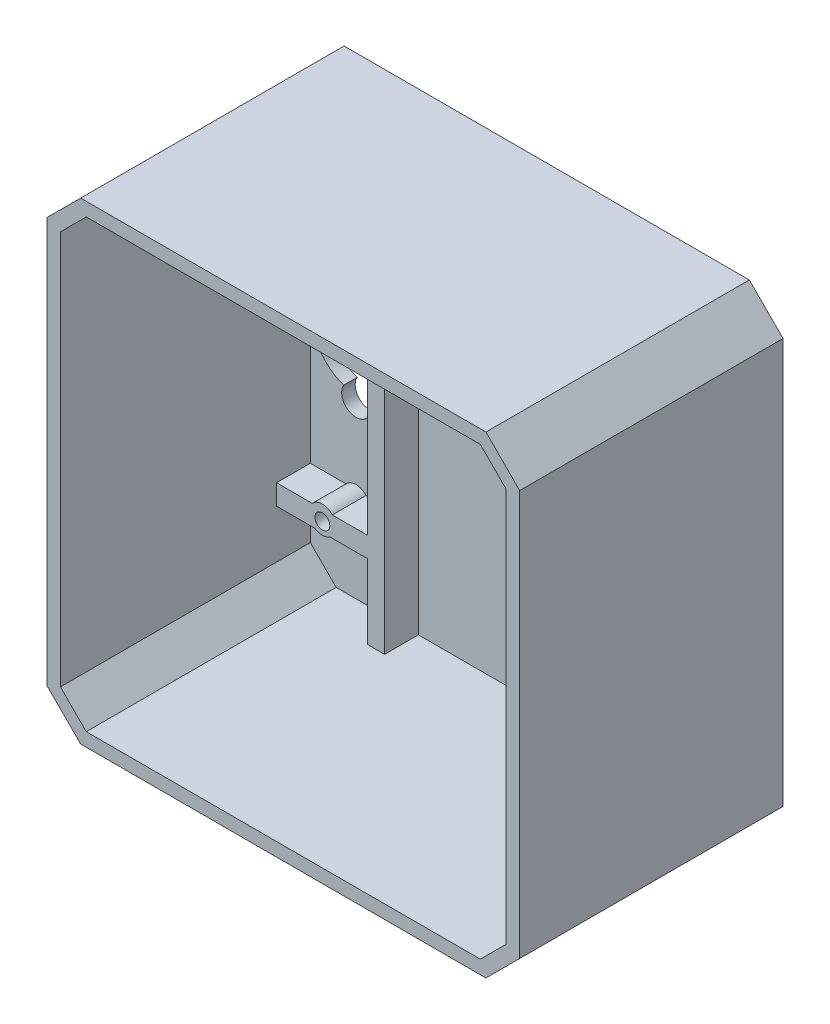
SolidWorks part; units mm, degrees
ref_plane "Front Plane" through (0, 0, 0) normal (0, 0, 1) x (1, 0, 0)
ref_plane "Top Plane" through (0, 0, 0) normal (0, 1, 0) x (1, 0, 0)
ref_plane "Right Plane" through (0, 0, 0) normal (1, 0, 0) x (0, 0, -1)
sketch "Sketch1" plane through (0, 0, 0) normal (0, 0, 1) x (1, 0, 0)
  line L1 (51.8222, 34.9266) -> (121.8222, 34.9266)
  line L2 (51.8222, 34.9266) -> (51.8222, -35.0734)
  line L3 (51.8222, -35.0734) -> (121.8222, -35.0734)
  line L4 (121.8222, 34.9266) -> (121.8222, -35.0734)
  dimension "D1" = 70
  dimension "D2" = 70
ref_plane "Plane1" through (0, 0, -39) normal (0, 0, 1) x (1, 0, 0)
extrude "Boss-Extrude1" add sketch "Sketch1" against normal blind 39
chamfer "Chamfer1" distance 5 angle 45 4 edges at (121.8222, -35.0734, -19.5) (51.8222, -35.0734, -19.5) (51.8222, 34.9266, -19.5) (121.8222, 34.9266, -19.5)
shell "Shell1" thickness 2
sketch "Sketch3" plane through (0, 0, -37) normal (0, 0, 1) x (1, 0, 0)
  line L0 (115.9938, 32.9266) -> (57.6506, 32.9266) construction
  line L1 (67.3222, 32.9266) -> (69.8222, 32.9266)
  line L2 (67.3222, 32.9266) -> (67.3222, -33.0734)
  line L3 (67.3222, -33.0734) -> (69.8222, -33.0734)
  line L4 (69.8222, 32.9266) -> (69.8222, -33.0734)
  line L5 (57.6506, -33.0734) -> (115.9938, -33.0734) construction
  line L6 (53.8222, 29.0982) -> (53.8222, -29.2449) construction
  line L8 (86.8222, 32.9266) -> (86.8222, -50.5449) construction
  line L9 (106.3222, -33.0734) -> (103.8222, -33.0734)
  line L10 (103.8222, 32.9266) -> (103.8222, -33.0734)
  line L11 (106.3222, 32.9266) -> (103.8222, 32.9266)
  line L12 (106.3222, 32.9266) -> (106.3222, -33.0734)
  dimension "D1" = 2.5
  dimension "D2" = 13.5
extrude "Boss-Extrude2" add sketch "Sketch3" along normal blind 5
sketch "Sketch4" plane through (0, 0, -37) normal (0, 0, 1) x (1, 0, 0)
  line L0 (53.8222, 29.0982) -> (53.8222, -29.2449) construction
  line L1 (53.8222, -19.0734) -> (67.3222, -19.0734)
  line L2 (53.8222, -19.0734) -> (53.8222, -22.0734)
  line L3 (53.8222, -22.0734) -> (67.3222, -22.0734)
  line L4 (67.3222, -19.0734) -> (67.3222, -22.0734)
  line L5 (67.3222, 32.9266) -> (67.3222, -33.0734) construction
  line L6 (57.6506, -33.0734) -> (67.3222, -33.0734) construction
  line L7 (53.8222, 29.0982) -> (53.8222, -29.2449) construction
  line L8 (53.8222, 9.9266) -> (67.3222, 9.9266)
  line L9 (53.8222, 9.9266) -> (53.8222, 6.9266)
  line L10 (53.8222, 6.9266) -> (67.3222, 6.9266)
  line L11 (67.3222, 9.9266) -> (67.3222, 6.9266)
  line L12 (86.8222, 32.9266) -> (86.8222, -49.2759) construction
  line L13 (103.8222, 32.9266) -> (69.8222, 32.9266) construction
  line L14 (119.8222, -22.0734) -> (106.3222, -22.0734)
  line L15 (106.3222, -19.0734) -> (106.3222, -22.0734)
  line L16 (119.8222, -19.0734) -> (106.3222, -19.0734)
  line L17 (119.8222, -19.0734) -> (119.8222, -22.0734)
  line L18 (119.8222, 6.9266) -> (106.3222, 6.9266)
  line L19 (106.3222, 9.9266) -> (106.3222, 6.9266)
  line L20 (119.8222, 9.9266) -> (106.3222, 9.9266)
  line L21 (119.8222, 9.9266) -> (119.8222, 6.9266)
  dimension "D1" = 3
  dimension "D2" = 14
  dimension "D3" = 26
  dimension "D4" = 3
extrude "Boss-Extrude3" add sketch "Sketch4" along normal up to surface (5 mm away) up to face at (68.5722, -0.0734, -32)
sketch "Sketch5" plane through (0, 0, -37) normal (0, 0, 1) x (1, 0, 0)
  line L0 (67.3222, 9.9266) -> (53.8222, 9.9266) construction
  line L1 (67.3222, 9.9266) -> (53.8222, 9.9266)
  line L2 (67.3222, 9.9266) -> (67.3222, 15.4266)
  line L3 (67.3222, 15.4266) -> (53.8222, 15.4266)
  line L4 (53.8222, 9.9266) -> (53.8222, 15.4266)
  line L5 (53.8222, 29.0982) -> (53.8222, -29.2449) construction
  line L6 (86.8222, -35.0734) -> (86.8222, -42.794) construction
  line L7 (56.8222, -35.0734) -> (116.8222, -35.0734) construction
  line L8 (106.3222, 15.4266) -> (119.8222, 15.4266)
  line L9 (119.8222, 9.9266) -> (119.8222, 15.4266)
  line L10 (106.3222, 9.9266) -> (119.8222, 9.9266)
  line L11 (106.3222, 9.9266) -> (106.3222, 15.4266)
  dimension "D1" = 5.5
extrude "Cut-Extrude1" cut sketch "Sketch5" against normal through all
sketch "Sketch6" plane through (0, 0, -37) normal (0, 0, 1) x (1, 0, 0)
  line L0 (86.8222, 32.9266) -> (86.8222, -44.1182) construction
  line L1 (53.8222, 6.9266) -> (67.3222, 6.9266) construction
  line L2 (103.8222, 32.9266) -> (69.8222, 32.9266) construction
  circle A0 centre (60.5866, -0.5734) radius 6.25
  circle A1 centre (113.0578, -0.5734) radius 6.25
  point P7 (60.5722, 6.9266)
  dimension "D1" = 12.5
  dimension "D2" = 7.5
extrude "Cut-Extrude2" cut sketch "Sketch6" against normal through all
sketch "Sketch8" plane through (0, 0, -37) normal (0, 0, 1) x (1, 0, 0)
  line L0 (58.7923, -6.5603) -> (62.3844, -6.5592)
  line L1 (86.8222, -35.0734) -> (86.8222, -45.0028) construction
  line L2 (56.8222, -35.0734) -> (116.8222, -35.0734) construction
  line L3 (114.8521, -6.5603) -> (111.26, -6.5592)
  arc A4 (58.7923, -6.5603) -> (62.3844, -6.5592) centre (60.5887, -7.686) ccw
  circle A5 centre (60.5866, -0.5734) radius 6.25 construction
  arc A6 (114.8521, -6.5603) -> (111.26, -6.5592) centre (113.0557, -7.686) cw
extrude "Cut-Extrude3" cut sketch "Sketch8" against normal blind 10
sketch "Sketch9" plane through (0, 0, -32) normal (0, 0, 1) x (1, 0, 0)
  line L0 (86.8222, -35.0734) -> (86.8222, -43.4105) construction
  line L1 (56.8222, -35.0734) -> (116.8222, -35.0734) construction
  circle A0 centre (60.5935, 8.4008) radius 2
  circle A1 centre (60.5935, -20.415) radius 2
  circle A2 centre (113.0508, -20.415) radius 2
  circle A3 centre (113.0508, 8.4008) radius 2
extrude "Boss-Extrude4" add sketch "Sketch9" against normal up to surface (5 mm away) up to face at (60.587, -2.0647, -37)
sketch "Sketch10" plane through (0, 0, -32) normal (0, 0, 1) x (1, 0, 0)
  line L0 (86.8222, -35.0734) -> (86.8222, -48.0105) construction
  line L1 (56.8222, -35.0734) -> (116.8222, -35.0734) construction
  circle A0 centre (60.6065, 8.3099) radius 1.1
  circle A1 centre (60.6065, -20.633) radius 1.1
  circle A2 centre (113.0379, -20.633) radius 1.1
  circle A3 centre (113.0379, 8.3099) radius 1.1
extrude "Cut-Extrude4" cut sketch "Sketch10" against normal blind 4
